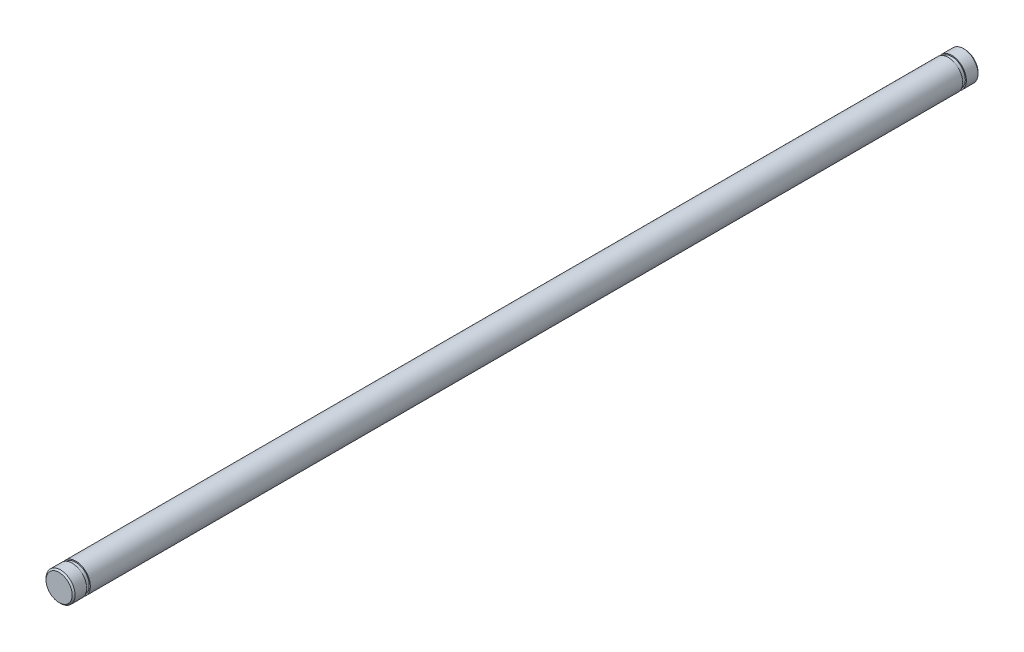
SolidWorks part; units mm, degrees
ref_plane "Vorne" through (0, 0, 0) normal (0, 0, 1) x (1, 0, 0)
ref_plane "Oben" through (0, 0, 0) normal (0, 1, 0) x (1, 0, 0)
ref_plane "Seite" through (0, 0, 0) normal (1, 0, 0) x (0, 0, -1)
sketch "Skizze1" plane through (0, 0, 0) normal (0, 0, 1) x (1, 0, 0)
  circle A0 centre (0, 0) radius 2
  point P3 (0, -3)
  dimension "D1" = 4
  dimension "D2" = 3
extrude "Aufsatz-Linear austragen1" add sketch "Skizze1" along normal mid plane 124.6
sketch "Skizze2" plane through (0, 0, 62.3) normal (0, 0, 1) x (1, 0, 0)
  point P0 (0, 0)
sketch "Skizze7" plane through (0, 0, 0) normal (1, 0, 0) x (0, 0, -1)
  line L0 (-60.5, 2) -> (-60.5, 1.85)
  line L1 (62.3, 2) -> (-62.3, 2) construction
  line L2 (-60.5, 1.85) -> (-60, 1.85)
  line L3 (-60, 1.85) -> (-60, 2)
  line L4 (-60, 2) -> (-60.5, 2)
  line L5 (60, 2) -> (60, 1.85)
  line L6 (60, 1.85) -> (60.5, 1.85)
  line L7 (60.5, 1.85) -> (60.5, 2)
  line L8 (60.5, 2) -> (60, 2)
  line L9 (-62.3, 2) -> (-62.3, -2) construction
  line L10 (62.3, 0) -> (-62.3, 0) construction
  line L11 (62.3, -2) -> (62.3, 2) construction
  dimension "D1" = 0.15
  dimension "D2" = 0.5
  dimension "D3" = 1.8
  dimension "D4" = 120
revolve "Schnitt-Rotation1" cut sketch "Skizze7" angle 360 about L10
chamfer "Fase1" distance 0.2 angle 45 2 edges at (2, 0, -62.3) (2, 0, 62.3)
